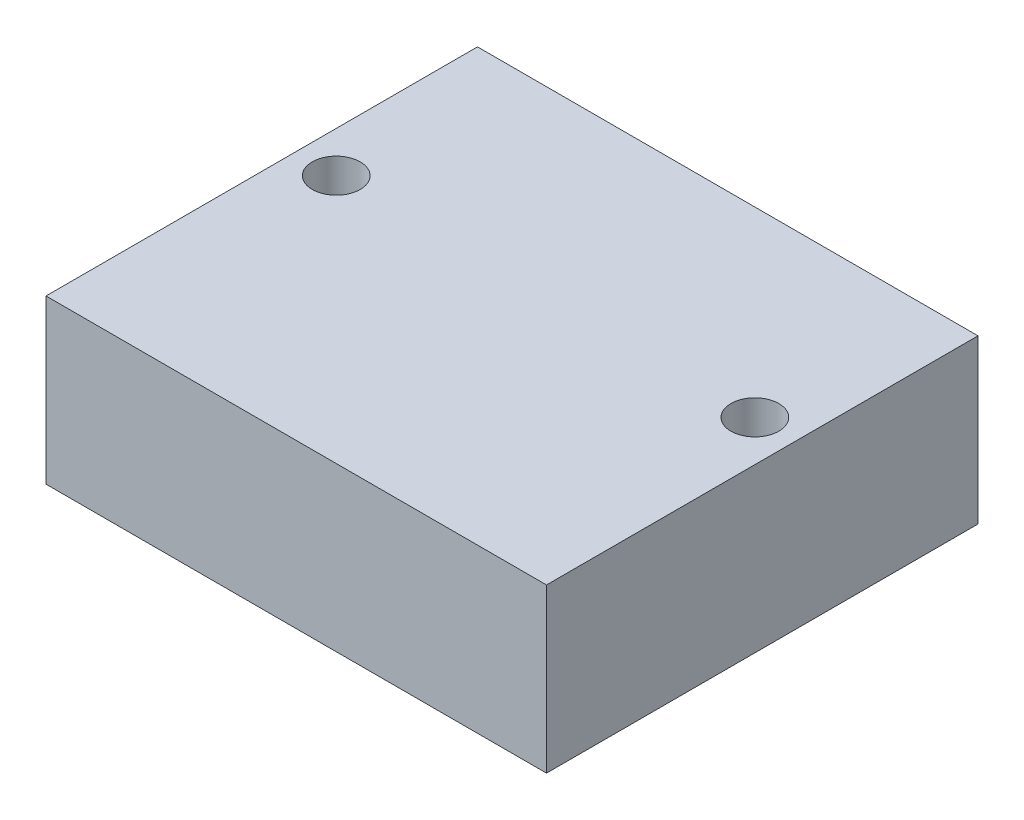
SolidWorks part; units mm, degrees
ref_plane "Front" through (0, 0, 0) normal (0, 0, 1) x (1, 0, 0)
ref_plane "Top" through (0, 0, 0) normal (0, 1, 0) x (1, 0, 0)
ref_plane "Right" through (0, 0, 0) normal (1, 0, 0) x (0, 0, -1)
sketch "Sketch1" plane through (0, 0, 0) normal (0, 1, 0) x (1, 0, 0)
  line L1 (-33.147, -28.575) -> (33.147, -28.575)
  line L2 (-33.147, -28.575) -> (-33.147, 28.575)
  line L3 (-33.147, 28.575) -> (33.147, 28.575)
  line L4 (33.147, -28.575) -> (33.147, 28.575)
  line L5 (-33.147, -28.575) -> (33.147, 28.575) construction
  line L6 (-33.147, 28.575) -> (33.147, -28.575) construction
  point P0 (0, 0)
  dimension "D1" = 66.294
  dimension "D2" = 57.15
extrude "Boss-Extrude1" add sketch "Sketch1" along normal blind 21.59
sketch "Sketch2" plane through (0, 21.59, 0) normal (0, 1, 0) x (1, 0, 0)
  line L0 (33.147, 28.575) -> (-33.147, 28.575) construction
  line L2 (-33.147, 28.575) -> (-33.147, -28.575) construction
  line L3 (0, -50) -> (0, 50) construction
  circle A0 centre (-27.7241, 4.445) radius 3.175
  circle A2 centre (27.7241, 4.445) radius 3.175
  point P8 (-27.7241, 4.445)
  dimension "D1" = 6.35
  dimension "D3" = 2.2479
  dimension "D2" = 24.13
extrude "Cut-Extrude1" cut sketch "Sketch2" against normal blind 21.59
